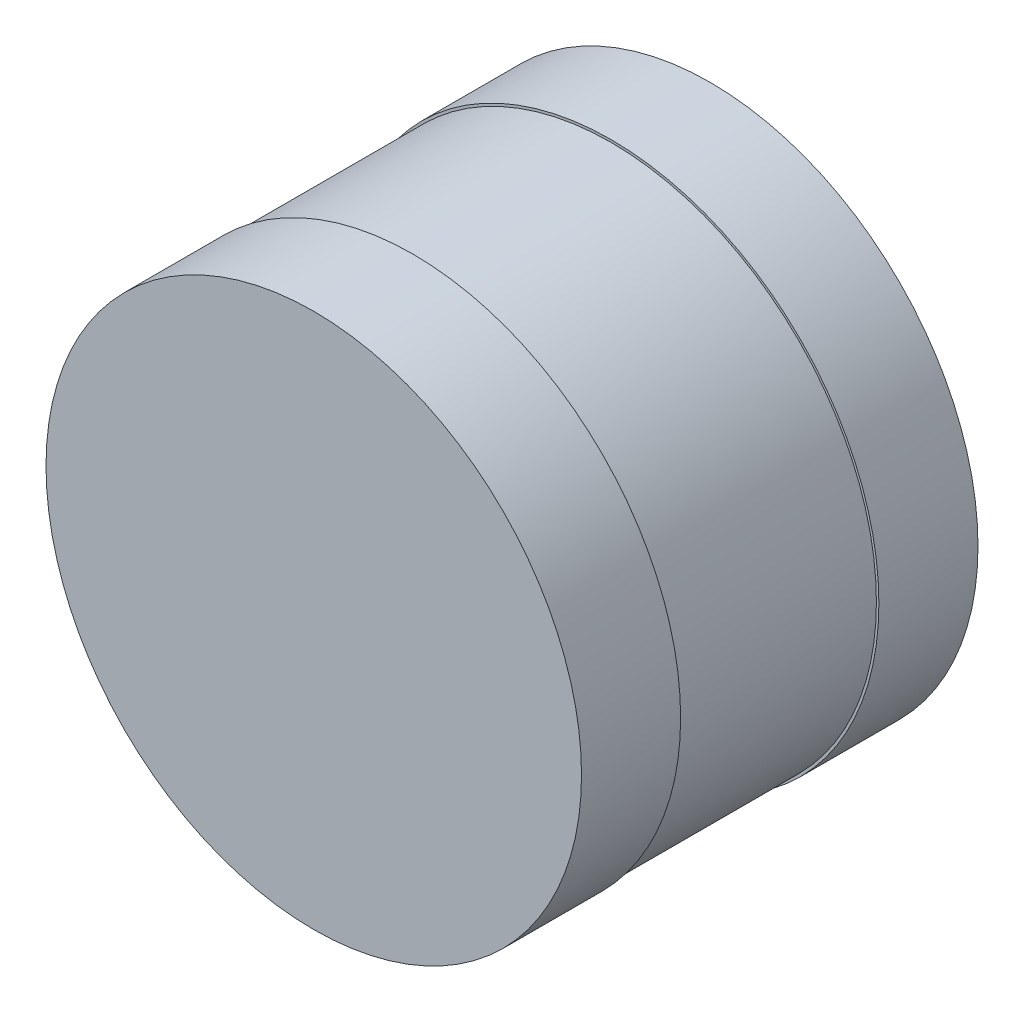
SolidWorks part; units mm, degrees
ref_plane "Front Plane" through (0, 0, 0) normal (0, 0, 1) x (1, 0, 0)
ref_plane "Top Plane" through (0, 0, 0) normal (0, 1, 0) x (1, 0, 0)
ref_plane "Right Plane" through (0, 0, 0) normal (1, 0, 0) x (0, 0, -1)
sketch "Sketch1" plane through (0, 0, 0) normal (0, 0, 1) x (1, 0, 0)
  circle A0 centre (0, 0) radius 54.5
  point P3 (-191.4924, -48.733)
extrude "Boss-Extrude3" add sketch "Sketch1" along normal blind 20.175
sketch "Sketch4" plane through (0, 0, 0) normal (0, 0, -1) x (-1, 0, 0)
  circle A0 centre (0, 0) radius 54
extrude "Boss-Extrude5" add sketch "Sketch4" along normal blind 40.35
sketch "Sketch5" plane through (0, 0, -40.35) normal (0, 0, -1) x (-1, 0, 0)
  circle A0 centre (0, 0) radius 54.5
extrude "Boss-Extrude6" add sketch "Sketch5" along normal blind 20.175
